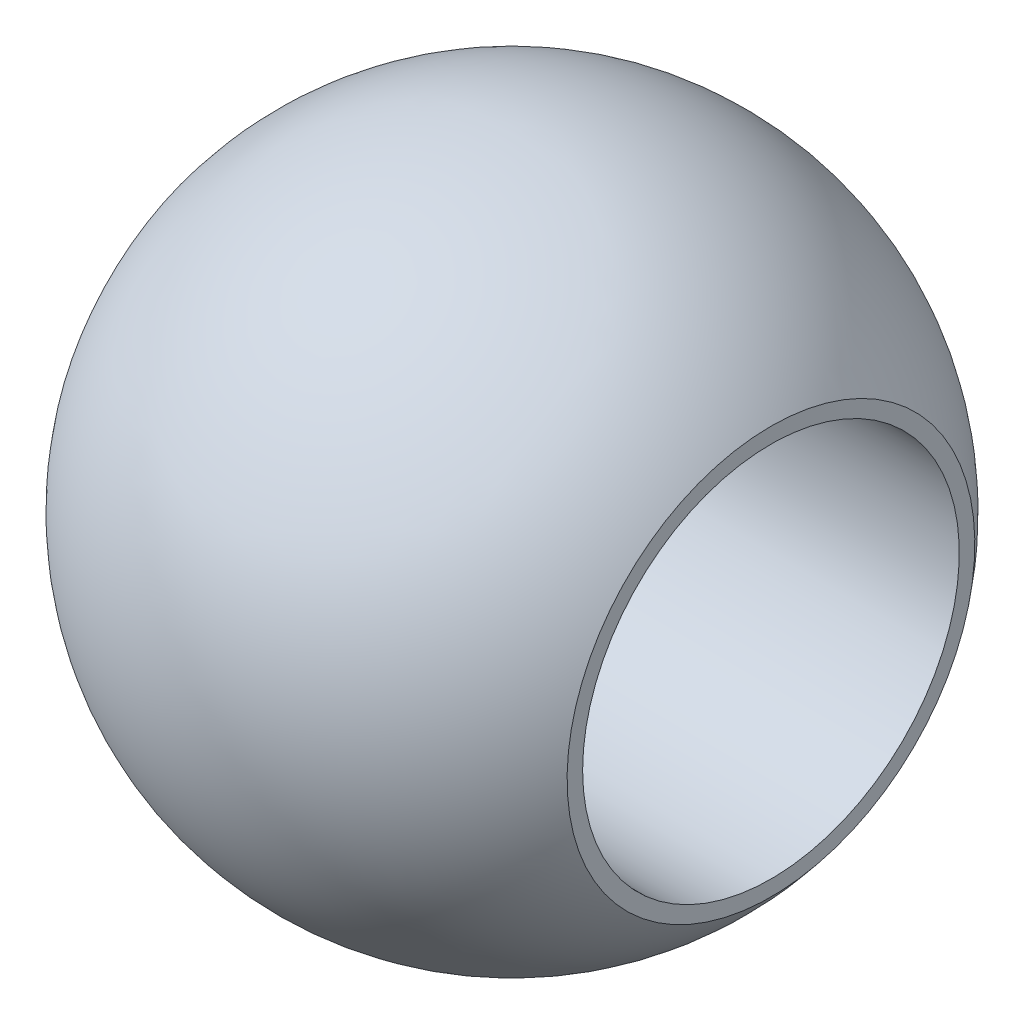
SolidWorks part; units mm, degrees
ref_plane "Face" through (0, 0, 0) normal (0, 0, 1) x (1, 0, 0)
ref_plane "Dessus" through (0, 0, 0) normal (0, 1, 0) x (1, 0, 0)
ref_plane "Droite" through (0, 0, 0) normal (1, 0, 0) x (0, 0, -1)
sketch "Esquisse1" plane through (0, 0, 0) normal (0, 0, 1) x (1, 0, 0)
  line L0 (0, 31.4817) -> (0, -36.5975) construction
  line L1 (-26.5416, 0) -> (30.0805, 0) construction
  line L2 (-5.5, 4) -> (5.5, 4)
  line L3 (5.5, 4.3301) -> (5.5, 4)
  line L4 (-5.5, 4.3301) -> (-5.5, 4)
  arc A0 (5.5, 4.3301) -> (-5.5, 4.3301) centre (0, 0) ccw
  point P11 (0, 4)
  dimension "D1" = 14
  dimension "D3" = 5.5
  dimension "D2" = 8
revolve "Base-Révolution" add sketch "Esquisse1" angle 360 about L1
